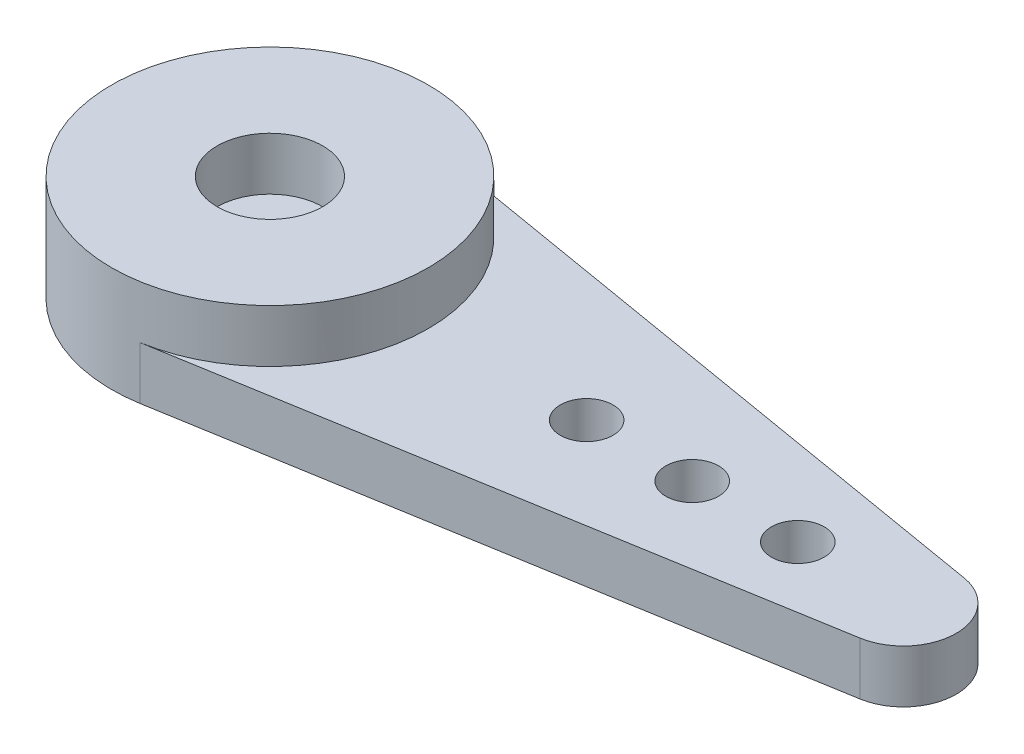
SolidWorks part; units mm, degrees
ref_plane "Front Plane" through (0, 0, 0) normal (0, 0, 1) x (1, 0, 0)
ref_plane "Top Plane" through (0, 0, 0) normal (0, 1, 0) x (1, 0, 0)
ref_plane "Right Plane" through (0, 0, 0) normal (1, 0, 0) x (0, 0, -1)
sketch "Sketch1" plane through (0, 0, 0) normal (0, 1, 0) x (1, 0, 0)
  line L0 (1.8167, 0) -> (60, 0) construction
  line L1 (2.5, 14.7902) -> (60.8333, 4.9301)
  line L2 (2.5, -14.7902) -> (60.8333, -4.9301)
  arc A0 (2.5, 14.7902) -> (2.5, -14.7902) centre (0, 0) ccw
  arc A1 (60.8333, -4.9301) -> (60.8333, 4.9301) centre (60, 0) ccw
  dimension "D1" = 30
  dimension "D2" = 10
  dimension "D3" = 60
extrude "Boss-Extrude1" add sketch "Sketch1" along normal blind 5
sketch "Sketch2" plane through (0, 5, 0) normal (0, 1, 0) x (1, 0, 0)
  circle A0 centre (0, 0) radius 15
  dimension "D1" = 30
extrude "Boss-Extrude2" add sketch "Sketch2" along normal blind 5
sketch "Sketch3" plane through (0, 10, 0) normal (0, 1, 0) x (1, 0, 0)
  circle A0 centre (0, 0) radius 5
  dimension "D1" = 10
extrude "Cut-Extrude1" cut sketch "Sketch3" against normal blind 5
sketch "Sketch4" plane through (0, 5, 0) normal (0, 1, 0) x (1, 0, 0)
  circle A0 centre (50, 0) radius 2.5
  circle A1 centre (40, 0) radius 2.5
  circle A2 centre (30, 0) radius 2.5
  dimension "D1" = 5
  dimension "D2" = 50
  dimension "D3" = 3
extrude "Cut-Extrude2" cut sketch "Sketch4" against normal blind 5
